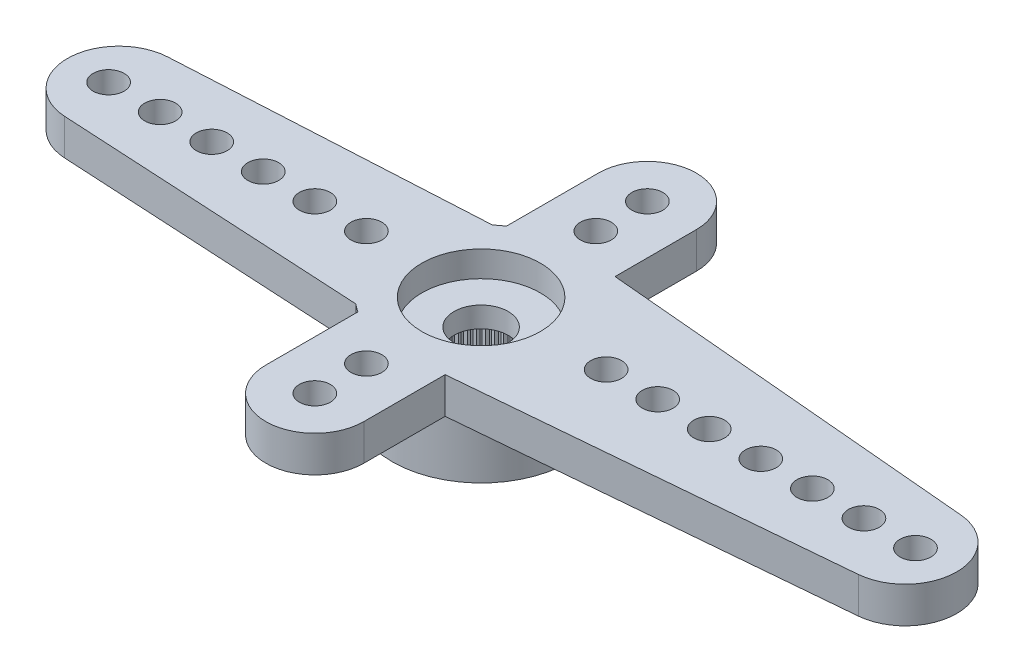
SolidWorks part; units mm, degrees
other "Markup1"
sketch "Sketch2" plane through (18.45, -3.8, 8.35) normal (0.5467, -0.076, 0.8339) x (0.3087, -0.9075, -0.285)
other "Markup2"
sketch "Sketch3" plane through (18.45, 0, 8.35) normal (0.5774, 0.5773, 0.5774) x (0.7071, 0, -0.7071)
material "PVC Rígido"
ref_plane "Plano frontal" through (0, 0, 0) normal (0, 0, 1) x (1, 0, 0)
ref_plane "Plano superior" through (0, 0, 0) normal (0, 1, 0) x (1, 0, 0)
ref_plane "Plano direito" through (0, 0, 0) normal (1, 0, 0) x (0, 0, -1)
sketch "Esboço1" plane through (0, 0, 0) normal (0, 1, 0) x (1, 0, 0)
  line L0 (0, 0) -> (-14.05, 0) construction
  line L1 (-14.1591, 1.997) -> (-2.2091, 2.65)
  line L2 (-2.2091, -2.65) -> (-14.1591, -1.997)
  arc A0 (-2.2091, -2.65) -> (-2.2091, 2.65) centre (0, 0) ccw
  arc A1 (-14.1591, 1.997) -> (-14.1591, -1.997) centre (-14.05, 0) ccw
  dimension "D1" = 6.9
  dimension "D2" = 4
  dimension "D3" = 19.5
  dimension "D4" = 5.3
extrude "Ressalto-extrusão1" add sketch "Esboço1" against normal blind 1.4
sketch "Esboço2" plane through (0, -1.4, 0) normal (0, -1, 0) x (1, 0, 0)
  arc A0 (-2.2091, -2.65) -> (-2.2091, 2.65) centre (0, 0) ccw construction
  circle A1 centre (0, 0) radius 3.45
extrude "Ressalto-extrusão2" add sketch "Esboço2" along normal offset from surface (2.4 mm away) 3.8 up to face at (-7.242, 0, 0)
hole_wizard "Furo1" positions "Esboço9" profile "Esboço10" legacy end condition through all
sketch "Esboço9" plane through (0, 0, 0) normal (0, 1, 0) x (1, 0, 0)
  line L1 (-14.45, 0) -> (0, 0) construction
  arc A2 (-14.1591, 1.997) -> (-14.1591, -1.997) centre (-14.05, 0) ccw construction
  point P0 (-14.45, 0)
  point P19 (-16.05, 0)
  dimension "D1" = 1.6
sketch "Esboço10" plane through (-14.45, 0, 0) normal (1, 0, 0) x (0, 0, 1)
  line L0 (0, 0) -> (0, 3.8)
  line L1 (0, 3.8) -> (0.6, 3.8)
  line L2 (0.6, 3.8) -> (0.6, 0)
  line L3 (0.6, 0) -> (0, 0)
  line L4 (0, 110) -> (0, -10) construction
  dimension "Diameter" = 1.2
  dimension "Depth" = 3.8
pattern_linear "Padrão linear1" count 6 spacing 2 along (1, 0, 0) of "Furo1"
sketch "Esboço12" plane through (0, 0, 0) normal (0, 1, 0) x (1, 0, 0)
  line L0 (0.3041, 3.4366) -> (16.6263, 1.9922)
  line L1 (16.6263, -1.9922) -> (0.3041, -3.4366)
  arc A0 (-2.2091, -2.65) -> (-2.2091, 2.65) centre (0, 0) ccw construction
  arc A1 (0.3041, -3.4366) -> (0.3041, 3.4366) centre (0, 0) ccw
  arc A2 (16.6263, 1.9922) -> (16.6263, -1.9922) centre (16.45, 0) cw
  arc A3 (-14.1591, 1.997) -> (-14.1591, -1.997) centre (-14.05, 0) ccw construction
  dimension "D1" = 2
  dimension "D2" = 34.5
extrude "Ressalto-extrusão3" add sketch "Esboço12" against normal up to surface (1.4 mm away) up to face at (-12.45, -1.4, 0.6)
hole_wizard "Furo2" positions "Esboço13" profile "Esboço14" legacy end condition through all
sketch "Esboço13" plane through (0, 0, 0) normal (0, 1, 0) x (1, 0, 0)
  line L0 (0, 0) -> (16.85, 0) construction
  arc A0 (16.6263, -1.9922) -> (16.6263, 1.9922) centre (16.45, 0) ccw construction
  point P0 (16.85, 0)
  point P6 (18.45, 0)
  dimension "D1" = 1.6
sketch "Esboço14" plane through (16.85, 0, 0) normal (1, 0, 0) x (0, 0, 1)
  line L0 (0, 0) -> (0, 3.8)
  line L1 (0, 3.8) -> (0.6, 3.8)
  line L2 (0.6, 3.8) -> (0.6, 0)
  line L3 (0.6, 0) -> (0, 0)
  line L4 (0, 110) -> (0, -10) construction
  dimension "Diameter" = 1.2
  dimension "Depth" = 3.8
pattern_linear "Padrão linear2" count 7 spacing 2 along (-1, 0, 0) of "Furo2"
sketch "Esboço16" plane through (0, 0, 0) normal (0, 1, 0) x (1, 0, 0)
  line L0 (0, -6.45) -> (0, 6.45) construction
  line L1 (-1.9, -6.45) -> (-1.9, 6.45)
  line L2 (1.9, -6.45) -> (1.9, 6.45)
  arc A0 (-1.9, -6.45) -> (1.9, -6.45) centre (0, -6.45) ccw
  arc A1 (1.9, 6.45) -> (-1.9, 6.45) centre (0, 6.45) ccw
  point P2 (0, 0)
  dimension "D2" = 16.7
  dimension "D1" = 3.8
extrude "Ressalto-extrusão4" add sketch "Esboço16" against normal up to surface (1.4 mm away) up to face at (14.85, -1.4, 0.6)
hole_wizard "Furo3" positions "Esboço17" profile "Esboço18" legacy end condition through all
sketch "Esboço17" plane through (0, 0, 0) normal (0, 1, 0) x (1, 0, 0)
  point P0 (0, -6.45)
sketch "Esboço18" plane through (0, 0, 6.45) normal (1, 0, 0) x (0, 0, 1)
  line L0 (0, 0) -> (0, 3.8)
  line L1 (0, 3.8) -> (0.6, 3.8)
  line L2 (0.6, 3.8) -> (0.6, 0)
  line L3 (0.6, 0) -> (0, 0)
  line L4 (0, 110) -> (0, -10) construction
  dimension "Diameter" = 1.2
  dimension "Depth" = 3.8
pattern_linear "Padrão linear3" count 2 spacing 2 along (0, 0, -1) of "Furo3"
pattern_circular "PadrãoCircular1" count 2 over 360 about axis through (0, 0, 0) along (0, 1, 0) of "Padrão linear3", "Furo3"
hole_wizard "Furo4" positions "Esboço3" profile "Esboço4" legacy
sketch "Esboço3" plane through (0, -3.8, 0) normal (0, -1, 0) x (-1, 0, 0)
  point P0 (0, 0)
sketch "Esboço4" plane through (0, -3.8, 0) normal (1, 0, 0) x (0, 0, -1)
  line L0 (0, 0) -> (0, 2)
  line L1 (0, 2) -> (2.475, 2)
  line L2 (2.475, 2) -> (2.475, 0)
  line L3 (2.475, 0) -> (0, 0)
  line L4 (0, 110) -> (0, -10) construction
  dimension "Diameter" = 4.95
  dimension "Depth" = 2
hole_wizard "Furo5" positions "Esboço5" profile "Esboço6" legacy
sketch "Esboço5" plane through (0, 0, 0) normal (0, 1, 0) x (1, 0, 0)
  point P0 (0, 0)
sketch "Esboço6" plane through (0, 0, 0) normal (1, 0, 0) x (0, 0, 1)
  line L0 (0, 0) -> (0, 1)
  line L1 (0, 1) -> (2.3, 1)
  line L2 (2.3, 1) -> (2.3, 0)
  line L3 (2.3, 0) -> (0, 0)
  line L4 (0, 110) -> (0, -10) construction
  dimension "Diameter" = 4.6
  dimension "Depth" = 1
hole_wizard "Furo6" positions "Esboço7" profile "Esboço8" legacy end condition through all
sketch "Esboço7" plane through (0, 0, 0) normal (0, 1, 0) x (1, 0, 0)
  point P0 (0, 0)
sketch "Esboço8" plane through (0, 0, 0) normal (1, 0, 0) x (0, 0, 1)
  line L0 (0, 0) -> (0, 3.8)
  line L1 (0, 3.8) -> (1.05, 3.8)
  line L2 (1.05, 3.8) -> (1.05, 0)
  line L3 (1.05, 0) -> (0, 0)
  line L4 (0, 110) -> (0, -10) construction
  dimension "Diameter" = 2.1
  dimension "Depth" = 3.8
sketch "Esboço11" plane through (0, -3.8, 0) normal (0, -1, 0) x (1, 0, 0)
  line L0 (-0.0981, 2.4731) -> (0, 2.375)
  line L1 (0, 2.375) -> (0.0981, 2.4731)
  line L2 (0, 0) -> (0, 2.475) construction
  circle A0 centre (0, 0) radius 2.375 construction
  circle A1 centre (0, 0) radius 2.475
  arc A2 (0.0981, 2.4731) -> (-0.0981, 2.4731) centre (0, 0) ccw
  dimension "D3" = 4.75
  dimension "D2" = 0.1
  dimension "D1" = 0
extrude "Ressalto-extrusão5" add sketch "Esboço11" against normal up to surface (2 mm away) up to face at (0, -1.8, 1.05)
pattern_circular "PadrãoCircular2" count 60 over 360 about axis through (0, 0, 0) along (0, 1, 0) of "Ressalto-extrusão5"
